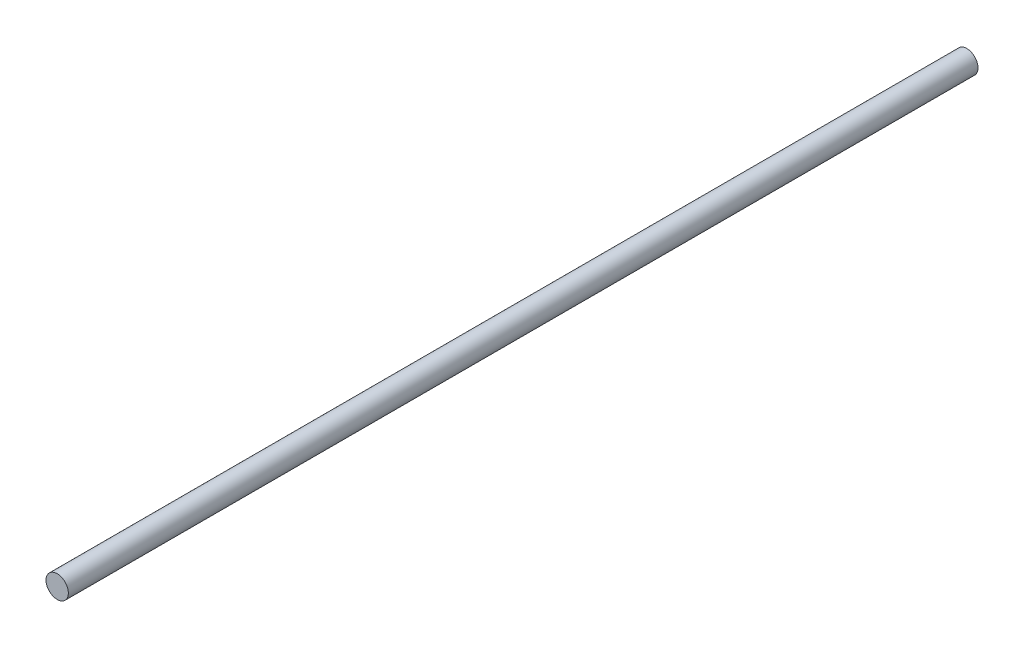
SolidWorks part; units mm, degrees
material "PVC 0.007 Plasticized"
ref_plane "Front Plane" through (0, 0, 0) normal (0, 0, 1) x (1, 0, 0)
ref_plane "Top Plane" through (0, 0, 0) normal (0, 1, 0) x (1, 0, 0)
ref_plane "Right Plane" through (0, 0, 0) normal (1, 0, 0) x (0, 0, -1)
sketch "Sketch1" plane through (0, 0, 0) normal (0, 0, 1) x (1, 0, 0)
  circle A0 centre (0, 0) radius 6
  dimension "D1" = 12
extrude "Boss-Extrude1" add sketch "Sketch1" along normal blind 488
